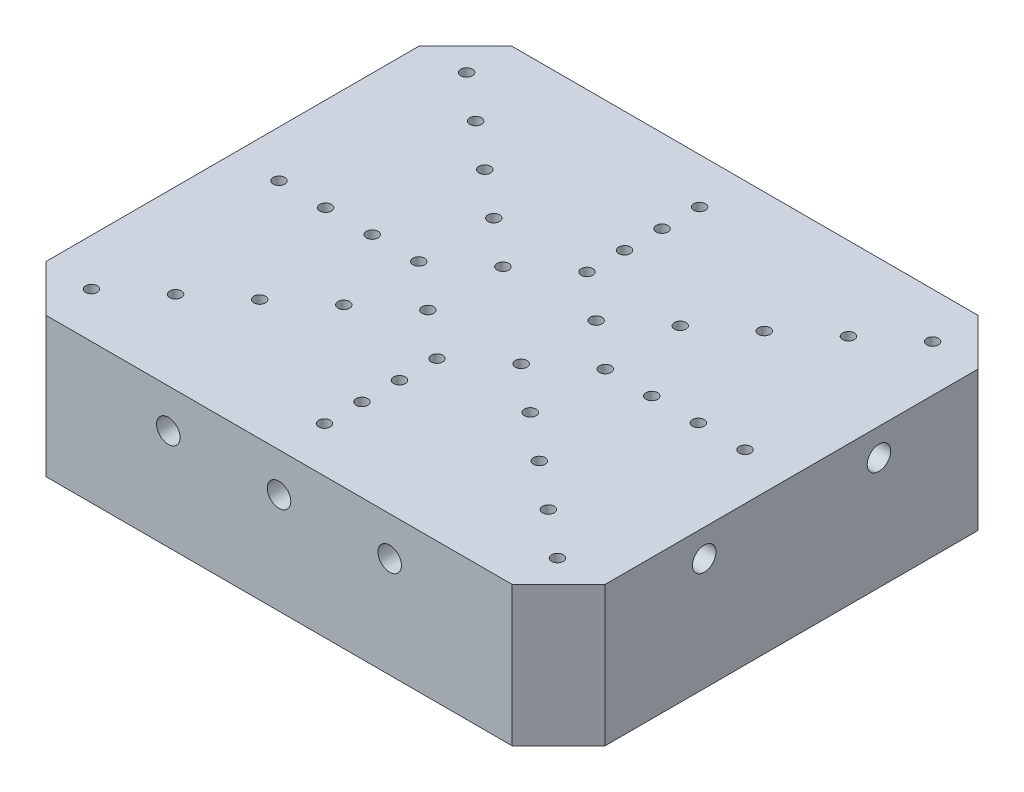
SolidWorks part; units mm, degrees
ref_plane "Front Plane" through (0, 0, 0) normal (0, 0, 1) x (1, 0, 0)
ref_plane "Top Plane" through (0, 0, 0) normal (0, 1, 0) x (1, 0, 0)
ref_plane "Right Plane" through (0, 0, 0) normal (1, 0, 0) x (0, 0, -1)
sketch "Sketch1" plane through (0, 0, 0) normal (0, 1, 0) x (1, 0, 0)
  line L1 (0, 0) -> (240, 0)
  line L2 (0, 0) -> (0, 200)
  line L3 (0, 200) -> (240, 200)
  line L4 (240, 0) -> (240, 200)
  line L5 (0, 0) -> (240, 200) construction
  line L6 (0, 200) -> (240, 0) construction
  point P4 (120, 100)
  dimension "D1" = 240
  dimension "D2" = 200
extrude "Boss-Extrude1" add sketch "Sketch1" along normal blind 60
chamfer "Chamfer1" distance 20 angle 45 4 edges at (0, 30, -200) (240, 30, -200) (240, 30, 0) (0, 30, 0)
sketch "Sketch2" plane through (0, 0, 0) normal (0, -1, 0) x (1, 0, 0)
  line L24 (10, -180) -> (10, -20)
  line L25 (10, -175) -> (10, -25)
  line L27 (20, -10) -> (220, -10)
  line L28 (25, -10) -> (215, -10)
  line L30 (230, -20) -> (230, -180)
  line L31 (230, -25) -> (230, -175)
  line L33 (220, -190) -> (20, -190)
  line L34 (215, -190) -> (25, -190)
  line L35 (215, -10) -> (230, -25)
  line L36 (10, -25) -> (25, -10)
  line L37 (25, -190) -> (10, -175)
  line L38 (230, -175) -> (215, -190)
  point P0 (230, -190)
  point P1 (10, -10)
  point P2 (10, -190)
  point P10 (230, -10)
  dimension "D1" = 10
  dimension "D2" = 10
  dimension "D3" = 10
  dimension "D4" = 10
extrude "Cut-Extrude1" cut sketch "Sketch2" against normal blind 56
ref_plane "Plane3" through (0, 55.8, 0) normal (0, -1, 0) x (-1, 0, 0)
sketch "Sketch21" plane through (0, 56, 0) normal (0, -1, 0) x (1, 0, 0)
  line L0 (120, -10) -> (120, -190) construction
  line L1 (215, -10) -> (25, -10) construction
  line L2 (25, -190) -> (215, -190) construction
  line L3 (17.5, -17.5) -> (222.5, -182.5) construction
  line L4 (25, -10) -> (10, -25) construction
  line L5 (215, -190) -> (230, -175) construction
  line L6 (222.5, -17.5) -> (17.5, -182.5) construction
  line L7 (230, -25) -> (215, -10) construction
  line L8 (10, -175) -> (25, -190) construction
  line L9 (10, -100) -> (230, -100) construction
  line L10 (10, -25) -> (10, -175) construction
  line L11 (230, -175) -> (230, -25) construction
  line L13 (220, -19.5122) -> (20, -19.5122) construction
  line L14 (220, -19.5122) -> (220, -180.4878) construction
  line L15 (220, -180.4878) -> (20, -180.4878) construction
  line L16 (20, -19.5122) -> (20, -180.4878) construction
  line L17 (120, -180.4878) -> (120, -19.5122) construction
  line L18 (220, -100) -> (20, -100) construction
  line L19 (200, -35.6098) -> (40, -35.6098) construction
  line L20 (200, -35.6098) -> (200, -164.3902) construction
  line L21 (200, -164.3902) -> (40, -164.3902) construction
  line L22 (40, -35.6098) -> (40, -164.3902) construction
  line L23 (120, -164.3902) -> (120, -35.6098) construction
  line L24 (200, -100) -> (40, -100) construction
  line L25 (180, -51.7073) -> (60, -51.7073) construction
  line L26 (180, -51.7073) -> (180, -148.2927) construction
  line L27 (180, -148.2927) -> (60, -148.2927) construction
  line L28 (60, -51.7073) -> (60, -148.2927) construction
  line L29 (120, -148.2927) -> (120, -51.7073) construction
  line L30 (180, -100) -> (60, -100) construction
  line L31 (80, -67.8049) -> (160, -67.8049) construction
  line L32 (80, -67.8049) -> (80, -132.1951) construction
  line L33 (80, -132.1951) -> (160, -132.1951) construction
  line L34 (160, -67.8049) -> (160, -132.1951) construction
  line L35 (120, -132.1951) -> (120, -67.8049) construction
  line L36 (80, -100) -> (160, -100) construction
  line L37 (100, -83.9024) -> (140, -83.9024) construction
  line L38 (100, -83.9024) -> (100, -116.0976) construction
  line L39 (100, -116.0976) -> (140, -116.0976) construction
  line L40 (140, -83.9024) -> (140, -116.0976) construction
  line L41 (120, -116.0976) -> (120, -83.9024) construction
  line L42 (100, -100) -> (140, -100) construction
  circle A0 centre (20, -19.5122) radius 2.5
  circle A1 centre (40, -35.6098) radius 2.5
  circle A2 centre (60, -51.7073) radius 2.5
  circle A3 centre (80, -67.8049) radius 2.5
  circle A4 centre (100, -83.9024) radius 2.5
  circle A5 centre (120, -19.5122) radius 2.5
  circle A6 centre (120, -35.6098) radius 2.5
  circle A7 centre (120, -51.7073) radius 2.5
  circle A8 centre (120, -67.8049) radius 2.5
  circle A10 centre (140, -83.9024) radius 2.5
  circle A11 centre (160, -67.8049) radius 2.5
  circle A12 centre (180, -51.7073) radius 2.5
  circle A13 centre (200, -35.6098) radius 2.5
  circle A14 centre (220, -19.5122) radius 2.5
  circle A15 centre (220, -100) radius 2.5
  circle A16 centre (200, -100) radius 2.5
  circle A17 centre (180, -100) radius 2.5
  circle A18 centre (160, -100) radius 2.5
  circle A20 centre (140, -116.0976) radius 2.5
  circle A21 centre (160, -132.1951) radius 2.5
  circle A22 centre (180, -148.2927) radius 2.5
  circle A23 centre (200, -164.3902) radius 2.5
  circle A24 centre (220, -180.4878) radius 2.5
  circle A25 centre (120, -180.4878) radius 2.5
  circle A26 centre (120, -164.3902) radius 2.5
  circle A27 centre (120, -148.2927) radius 2.5
  circle A28 centre (120, -132.1951) radius 2.5
  circle A30 centre (100, -116.0976) radius 2.5
  circle A31 centre (80, -132.1951) radius 2.5
  circle A32 centre (60, -148.2927) radius 2.5
  circle A33 centre (40, -164.3902) radius 2.5
  circle A34 centre (20, -180.4878) radius 2.5
  circle A35 centre (20, -100) radius 2.5
  circle A36 centre (40, -100) radius 2.5
  circle A37 centre (60, -100) radius 2.5
  circle A38 centre (80, -100) radius 2.5
  point P24 (120, -100)
  point P28 (120, -100)
  point P32 (120, -100)
  point P36 (120, -100)
  point P40 (120, -100)
  dimension "D6" = 5
  dimension "D1" = 10
  dimension "D2" = 20
  dimension "D3" = 20
  dimension "D4" = 20
  dimension "D5" = 20
extrude "Cut-Extrude16" cut sketch "Sketch21" against normal blind 54
sketch "Sketch24" plane through (0, 0, -190) normal (0, 0, 1) x (1, 0, 0)
  line L0 (120, 0) -> (120, 56) construction
  line L6 (25, 0) -> (215, 0) construction
  line L8 (117.5, 56) -> (122.5, 56) construction
  line L11 (25, 43.3) -> (120, 43.3) construction
  line L12 (25, 56) -> (25, 0) construction
  line L13 (120, 43.3) -> (215, 43.3) construction
  line L14 (215, 56) -> (215, 0) construction
  line L15 (25, 56) -> (215, 56) construction
  circle A1 centre (120, 43.3) radius 5.05
  circle A2 centre (72.5, 43.3) radius 5.05
  circle A3 centre (167.5, 43.3) radius 5.05
  dimension "D1" = 12.7
  dimension "D2" = 10.1
extrude "Cut-Extrude17" cut sketch "Sketch24" against normal through all both and the other way through all
sketch "Sketch27" plane through (10, 0, 0) normal (1, 0, 0) x (0, 0, -1)
  line L0 (100, 0) -> (100, 56) construction
  line L1 (25, 0) -> (175, 0) construction
  line L2 (25, 56) -> (175, 56) construction
  line L3 (25, 48.3) -> (100, 48.3) construction
  line L4 (25, 56) -> (25, 0) construction
  line L5 (100, 48.3) -> (175, 48.3) construction
  line L6 (175, 56) -> (175, 0) construction
  circle A0 centre (62.5, 48.3) radius 5.05
  circle A1 centre (137.5, 48.3) radius 5.05
  dimension "D2" = 10.1
  dimension "D1" = 7.7
extrude "Cut-Extrude18" cut sketch "Sketch27" against normal through all both and the other way through all
sketch "Sketch25" plane through (0, 0, -200) normal (0, 0, -1) x (-1, 0, 0)
  circle A0 centre (-167.5, 43.3) radius 15 construction
  circle A1 centre (-167.5, 10.3) radius 15 construction
  dimension "D1" = 30
  dimension "D2" = 33
sketch "Sketch29" plane through (0, 0, -200) normal (0, 0, -1) x (-1, 0, 0)
  circle A0 centre (-167.5, 10.3) radius 5.05 construction
  dimension "D1" = 10.1
sketch "Sketch30" plane through (0, 56, 0) normal (0, -1, 0) x (1, 0, 0)
  circle A0 centre (200, -35.6098) radius 5
  dimension "D1" = 10
extrude "Boss-Extrude2" add sketch "Sketch30" along normal blind 8.53 separate body
